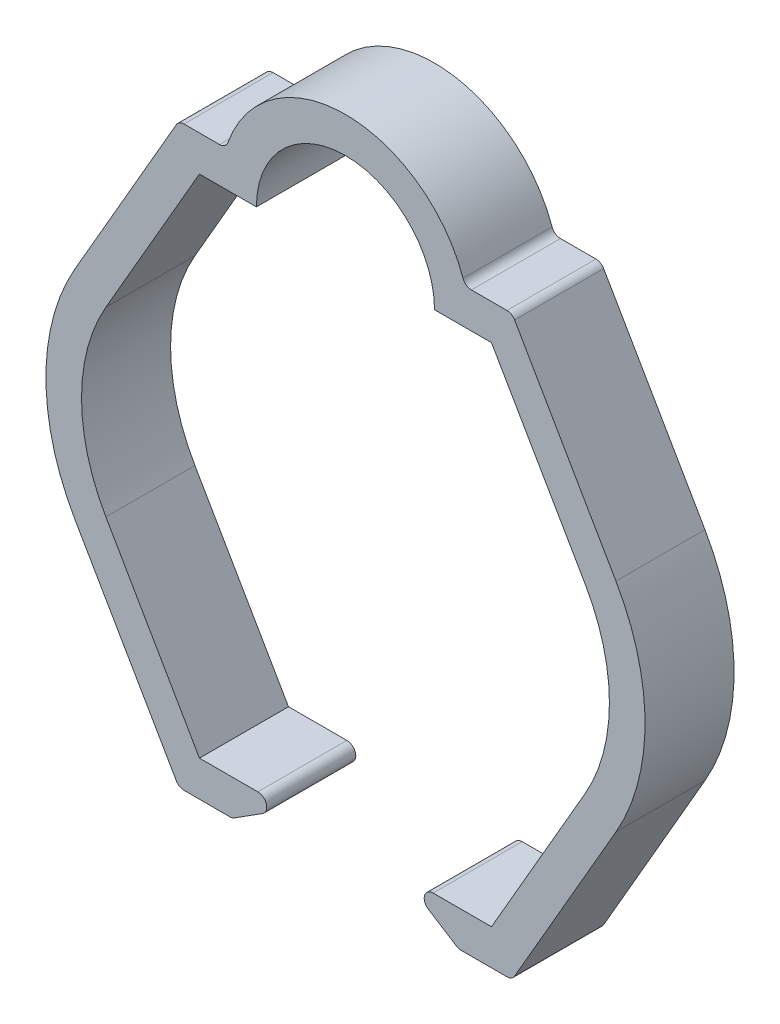
SolidWorks part; units mm, degrees
ref_plane "Front Plane" through (0, 0, 0) normal (0, 0, 1) x (1, 0, 0)
ref_plane "Top Plane" through (0, 0, 0) normal (0, 1, 0) x (1, 0, 0)
ref_plane "Right Plane" through (0, 0, 0) normal (1, 0, 0) x (0, 0, -1)
sketch "Sketch1" plane through (0, 0, 0) normal (0, 0, 1) x (1, 0, 0)
  line L12 (-57.8622, -29.798) -> (-52.6661, -38.798) construction
  line L13 (-52.6661, -38.798) -> (-36.5003, -38.798) construction
  line L14 (-36.5003, -38.798) -> (-31.3041, -29.798) construction
  line L15 (-31.3041, -19.798) -> (-36.5003, -10.798) construction
  line L16 (-36.5003, -10.798) -> (-52.6661, -10.798) construction
  line L17 (-52.6661, -10.798) -> (-57.8622, -19.798) construction
  line L18 (-58.0354, -29.898) -> (-52.7815, -38.998)
  line L19 (-52.7815, -38.998) -> (-47.7815, -38.998)
  line L23 (-52.7815, -10.598) -> (-58.0354, -19.698)
  line L24 (-59.7675, -30.898) -> (-53.9362, -40.998)
  line L25 (-53.9362, -40.998) -> (-50.9362, -40.998)
  line L29 (-53.9362, -8.598) -> (-59.7675, -18.698)
  line L30 (-50.9362, -40.998) -> (-47.7815, -38.998)
  line L32 (-44.5832, -5.598) -> (-44.5832, -3.598)
  line L33 (-51.2914, -8.598) -> (-53.9362, -8.598)
  line L34 (-35.2301, -8.598) -> (-53.9362, -8.598) construction
  line L35 (-49.5832, -10.598) -> (-52.7815, -10.598)
  line L36 (-36.3848, -10.598) -> (-52.7815, -10.598) construction
  line L37 (-29.3988, -18.698) -> (-35.2301, -8.598) construction
  line L38 (-31.1309, -19.698) -> (-36.3848, -10.598) construction
  line L39 (-35.2301, -40.998) -> (-29.3988, -30.898) construction
  line L40 (-36.3848, -38.998) -> (-31.1309, -29.898) construction
  line L41 (-53.9362, -40.998) -> (-35.2301, -40.998) construction
  line L42 (-52.7815, -38.998) -> (-36.3848, -38.998) construction
  arc A4 (-57.8622, -19.798) -> (-57.8622, -29.798) centre (-49.202, -24.798) ccw construction
  arc A5 (-31.3041, -29.798) -> (-31.3041, -19.798) centre (-39.9644, -24.798) ccw construction
  arc A7 (-58.0354, -19.698) -> (-58.0354, -29.898) centre (-49.202, -24.798) ccw
  arc A8 (-59.7675, -18.698) -> (-59.7675, -30.898) centre (-49.202, -24.798) ccw
  arc A10 (-44.5832, -5.598) -> (-49.5832, -10.598) centre (-44.5832, -10.598) ccw
  arc A11 (-44.5832, -3.598) -> (-51.2914, -8.598) centre (-44.5832, -10.598) ccw
  arc A14 (-29.3988, -30.898) -> (-29.3988, -18.698) centre (-39.9644, -24.798) ccw construction
  arc A15 (-31.1309, -29.898) -> (-31.1309, -19.698) centre (-39.9644, -24.798) ccw construction
  point P34 (0, 0)
  dimension "D1" = 10
  dimension "D11" = 2
  dimension "D12" = 10
  dimension "D2" = 31.3041
  dimension "D3" = 36.5003
  dimension "D4" = 39.9644
  dimension "D5" = 49.202
  dimension "D6" = 10.798
  dimension "D7" = 0.2
  dimension "D8" = 2
  dimension "D9" = 3
  dimension "D10" = 5
  dimension "D13" = 5
  dimension "D14" = 3.1984
  dimension "D15" = 2.6449
extrude "Boss-Extrude1" add sketch "Sketch1" along normal blind 5
mirror "Mirror1" about plane through (-44.5832, -5.598, 5) normal (-1, 0, 0) of "Boss-Extrude1"
fillet "Fillet1" radius 0.5 10 edges at (-41.3848, -38.998, 2.5) (-47.7815, -38.998, 2.5) (-37.875, -8.598, 2.5) (-35.2301, -8.598, 2.5) (-35.2301, -40.998, 2.5) (-38.2301, -40.998, 2.5) (-50.9362, -40.998, 2.5) (-53.9362, -40.998, 2.5) (-53.9362, -8.598, 2.5) (-51.2914, -8.598, 2.5)
